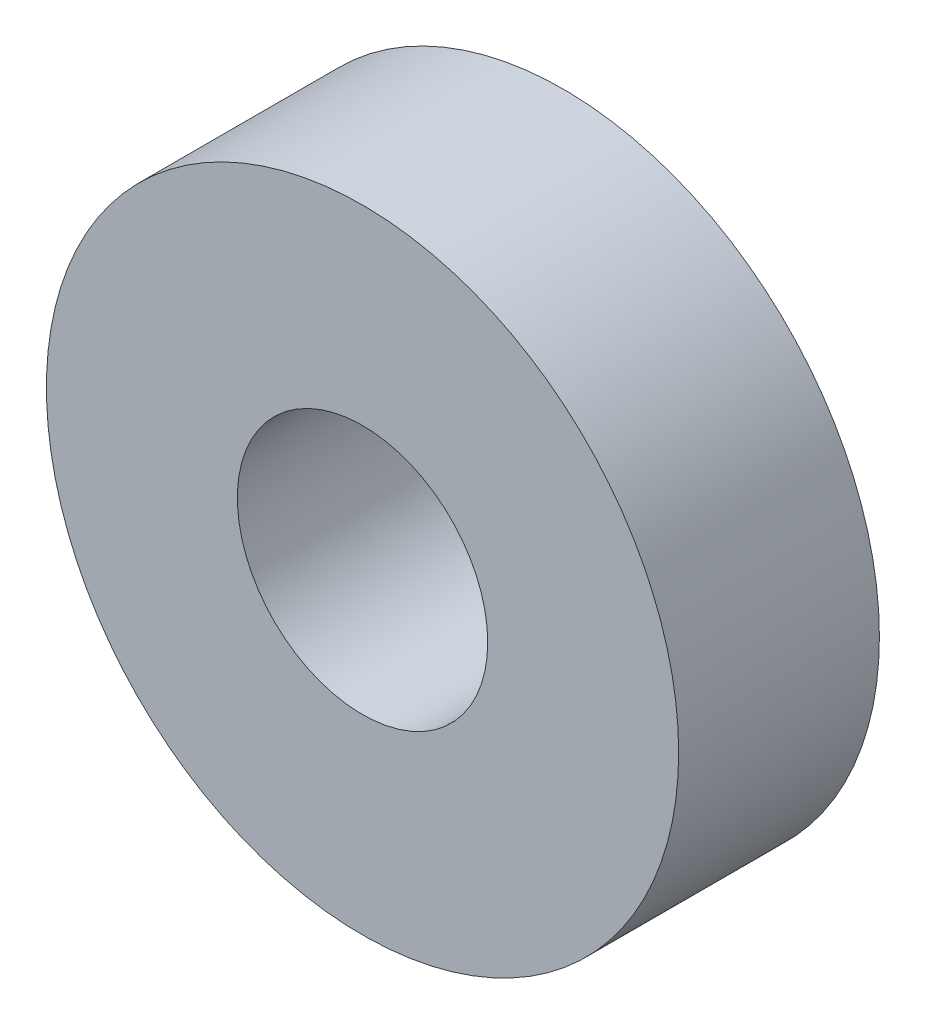
SolidWorks part; units mm, degrees
ref_plane "Plan de face" through (0, 0, 0) normal (0, 0, 1) x (1, 0, 0)
ref_plane "Plan de dessus" through (0, 0, 0) normal (0, 1, 0) x (1, 0, 0)
ref_plane "Plan de droite" through (0, 0, 0) normal (1, 0, 0) x (0, 0, -1)
sketch "Esquisse1" plane through (0, 0, 0) normal (0, 0, 1) x (1, 0, 0)
  circle A0 centre (0, 0) radius 10
  circle A1 centre (0, 0) radius 3.96
  dimension "D1" = 20
  dimension "D2" = 7.92
extrude "Boss.-Extru.1" add sketch "Esquisse1" along normal blind 6.35
